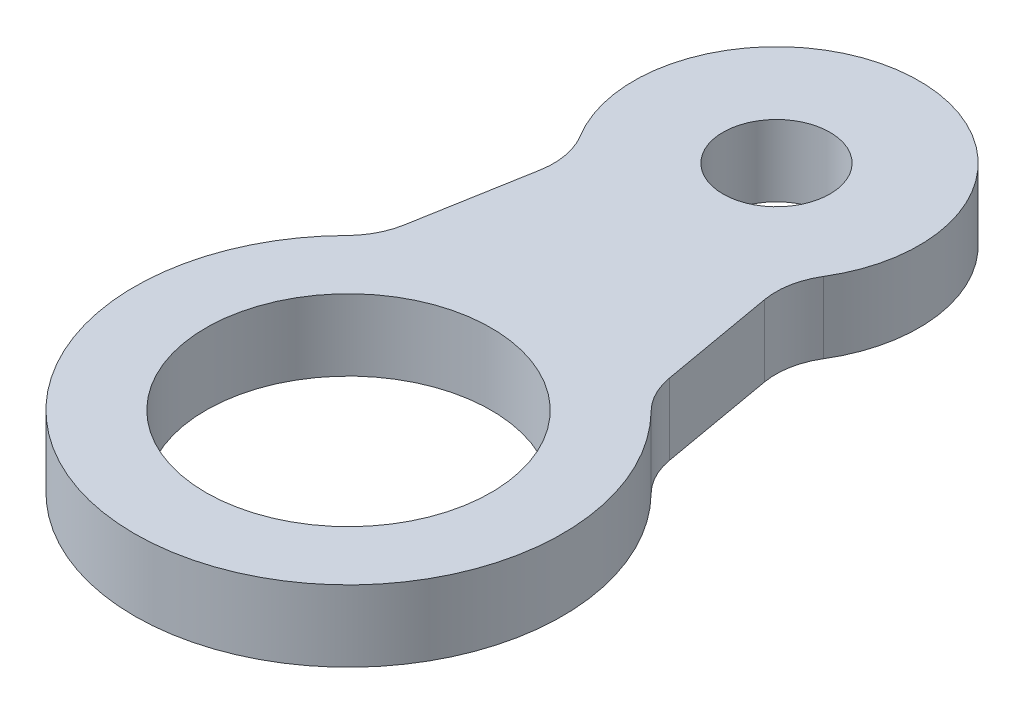
SolidWorks part; units mm, degrees
ref_plane "Front Plane" through (0, 0, 0) normal (0, 0, 1) x (1, 0, 0)
ref_plane "Top Plane" through (0, 0, 0) normal (0, 1, 0) x (1, 0, 0)
ref_plane "Right Plane" through (0, 0, 0) normal (1, 0, 0) x (0, 0, -1)
sketch "Sketch1" plane through (0, 0, 0) normal (0, 1, 0) x (1, 0, 0)
  line L0 (0, 0) -> (0, 76.2) construction
  line L5 (-24.3579, 29.2968) -> (-19.05, 59.3995)
  line L6 (24.3579, 29.2968) -> (19.05, 59.3995)
  arc A0 (-24.3579, 29.2968) -> (24.3579, 29.2968) centre (0, 0) ccw
  circle A1 centre (0, 0) radius 25.4
  arc A2 (19.05, 59.3995) -> (-19.05, 59.3995) centre (0, 76.2) ccw
  circle A3 centre (0, 76.2) radius 9.525
  dimension "D1" = 25.4
  dimension "D2" = 38.1
  dimension "D6" = 19.05
  dimension "D7" = 12.7
  dimension "D3" = 10
  dimension "D4" = 38.1
  dimension "D5" = 76.2
extrude "Boss-Extrude1" add sketch "Sketch1" along normal blind 12.7
fillet "Fillet1" radius 12.7 4 edges at (19.05, 6.35, -59.3995) (-24.3579, 6.35, -29.2968) (-19.05, 6.35, -59.3995) (24.3579, 6.35, -29.2968)
sketch "Sketch2" plane through (0, 12.7, 0) normal (0, 1, 0) x (1, 0, 0)
  line L0 (12.7, -35.921) -> (12.7, -50.8)
  line L1 (12.7, -50.8) -> (25.4, -50.8)
  line L2 (25.4, -50.8) -> (25.4, -63.5)
  line L3 (25.4, -63.5) -> (-25.4, -63.5)
  line L4 (0, 0) -> (0, -63.5) construction
  line L5 (-25.4, -50.8) -> (-25.4, -63.5)
  line L6 (-12.7, -50.8) -> (-25.4, -50.8)
  line L7 (-12.7, -35.921) -> (-12.7, -50.8)
  arc A0 (-27.091, 26.7897) -> (27.091, 26.7897) centre (0, 0) ccw construction
  arc A1 (-12.7, -35.921) -> (12.7, -35.921) centre (0, 0) ccw
  dimension "D1" = 12.7
  dimension "D2" = 63.5
  dimension "D3" = 25.4
  dimension "D4" = 12.7
ref_plane "Plane1" through (0, -20.32, 0) normal (0, 1, 0) x (1, 0, 0)
sketch "Sketch3" plane through (0, -20.32, 0) normal (0, 1, 0) x (1, 0, 0)
  line L0 (-12.7, -35.921) -> (-12.7, -50.8) construction
  line L1 (-12.7, -50.8) -> (-25.4, -50.8) construction
  line L2 (23.6143, 33.5143) -> (19.9848, 54.0978)
  line L3 (-19.9848, 54.0978) -> (-23.6143, 33.5143)
  line L4 (23.6143, 33.5143) -> (19.9848, 54.0978)
  line L5 (-19.9848, 54.0978) -> (-23.6143, 33.5143)
  line L6 (-25.4, -50.8) -> (-25.4, -63.5) construction
  line L7 (25.4, -63.5) -> (-25.4, -63.5) construction
  line L8 (25.4, -50.8) -> (25.4, -63.5) construction
  line L9 (12.7, -50.8) -> (25.4, -50.8) construction
  line L10 (12.7, -35.921) -> (12.7, -50.8) construction
  line L11 (-12.7, -35.921) -> (-12.7, -50.8)
  line L12 (-12.7, -50.8) -> (-25.4, -50.8)
  line L13 (-25.4, -50.8) -> (-25.4, -63.5)
  line L14 (25.4, -63.5) -> (-25.4, -63.5)
  line L15 (25.4, -50.8) -> (25.4, -63.5)
  line L16 (12.7, -50.8) -> (25.4, -50.8)
  line L17 (12.7, -35.921) -> (12.7, -50.8)
  circle A0 centre (0, 0) radius 25.4 construction
  circle A1 centre (0, 0) radius 25.4
  circle A2 centre (0, 76.2) radius 9.525 construction
  circle A3 centre (0, 76.2) radius 9.525
  arc A4 (-12.7, -35.921) -> (12.7, -35.921) centre (0, 0) ccw construction
  arc A5 (-12.7, -35.921) -> (12.7, -35.921) centre (0, 0) ccw
  arc A6 (21.6613, 62.9354) -> (-21.6613, 62.9354) centre (0, 76.2) ccw
  arc A7 (21.6613, 62.9354) -> (19.9848, 54.0978) centre (32.4919, 56.3031) ccw
  arc A8 (23.6143, 33.5143) -> (27.091, 26.7897) centre (36.1213, 35.7196) ccw
  arc A9 (-27.091, 26.7897) -> (27.091, 26.7897) centre (0, 0) ccw
  arc A10 (-27.091, 26.7897) -> (-23.6143, 33.5143) centre (-36.1213, 35.7196) ccw
  arc A11 (-19.9848, 54.0978) -> (-21.6613, 62.9354) centre (-32.4919, 56.3031) ccw
  arc A12 (21.6613, 62.9354) -> (-21.6613, 62.9354) centre (0, 76.2) ccw
  arc A13 (21.6613, 62.9354) -> (19.9848, 54.0978) centre (32.4919, 56.3031) ccw
  arc A14 (23.6143, 33.5143) -> (27.091, 26.7897) centre (36.1213, 35.7196) ccw
  arc A15 (-27.091, 26.7897) -> (27.091, 26.7897) centre (0, 0) ccw
  arc A16 (-27.091, 26.7897) -> (-23.6143, 33.5143) centre (-36.1213, 35.7196) ccw
  arc A17 (-19.9848, 54.0978) -> (-21.6613, 62.9354) centre (-32.4919, 56.3031) ccw
  dimension "D1" = 0
